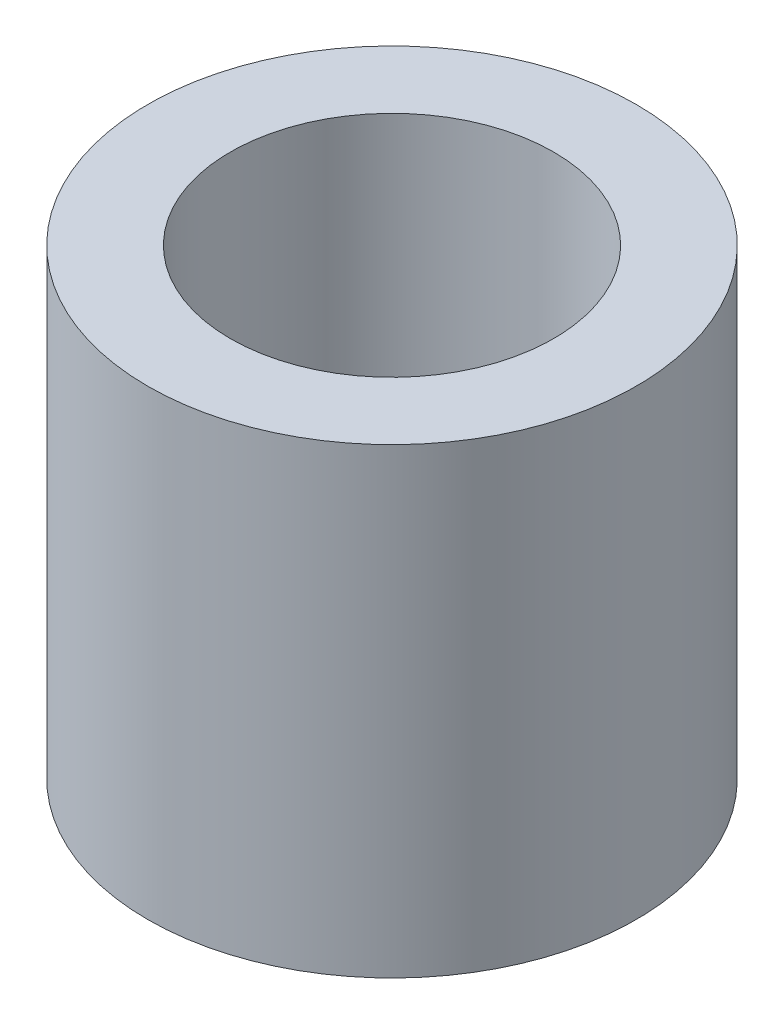
SolidWorks part; units mm, degrees
ref_plane "Front Plane" through (0, 0, 0) normal (0, 0, 1) x (1, 0, 0)
ref_plane "Top Plane" through (0, 0, 0) normal (0, 1, 0) x (1, 0, 0)
ref_plane "Right Plane" through (0, 0, 0) normal (1, 0, 0) x (0, 0, -1)
sketch "Sketch1" plane through (0, 0, 0) normal (0, 1, 0) x (1, 0, 0)
  circle A0 centre (0, 0) radius 7.4
  dimension "D1" = 14.8
extrude "Boss-Extrude1" add sketch "Sketch1" along normal blind 14
sketch "Sketch2" plane through (0, 14, 0) normal (0, 1, 0) x (1, 0, 0)
  circle A3 centre (0, 0) radius 4.9
  circle A4 centre (0, 0) radius 4.9
  dimension "D1" = 2.5
extrude "Cut-Extrude1" cut sketch "Sketch2" against normal through all
equation "\"HEIGHT\"= 14"
equation "\"D1@Boss-Extrude1\"=\"HEIGHT\""
